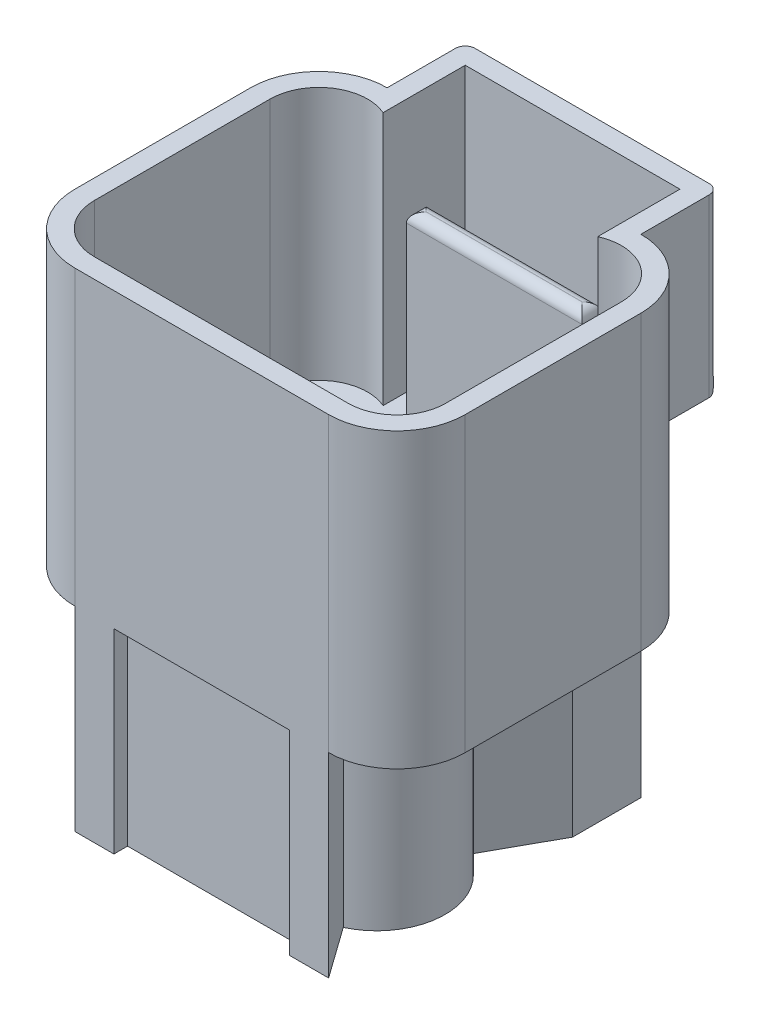
SolidWorks part; units mm, degrees
ref_plane "正面" through (0, 0, 0) normal (0, 0, 1) x (1, 0, 0)
ref_plane "平面" through (0, 0, 0) normal (0, 1, 0) x (1, 0, 0)
ref_plane "右側面" through (0, 0, 0) normal (1, 0, 0) x (0, 0, -1)
sketch "ｽｹｯﾁ1" plane through (0, 0, 0) normal (0, 0, 1) x (1, 0, 0)
  line L1 (0, 0) -> (20, 0)
  line L2 (0, 0) -> (0, 15)
  line L3 (0, 15) -> (20, 15)
  line L4 (20, 0) -> (20, 15)
  dimension "D1" = 20
  dimension "D2" = 15
extrude "ﾎﾞｽ - 押し出し1" add sketch "ｽｹｯﾁ1" along normal blind 16
fillet "ﾌｨﾚｯﾄ1" radius 3.5 4 edges at (0, 7.5, 16) (0, 7.5, 0) (20, 7.5, 16) (20, 7.5, 0)
sketch "ｽｹｯﾁ2" plane through (0, 0, 0) normal (0, 0, -1) x (-1, 0, 0)
  line L0 (-3.5, 0) -> (-3.5, 15) construction
  line L1 (-16.5, 15) -> (-3.5, 15)
  line L2 (-16.5, 15) -> (-16.5, 6)
  line L3 (-16.5, 6) -> (-3.5, 6)
  line L4 (-3.5, 15) -> (-3.5, 6)
  dimension "D1" = 9
extrude "ﾎﾞｽ - 押し出し2" add sketch "ｽｹｯﾁ2" along normal blind 4
fillet "ﾌｨﾚｯﾄ2" radius 0.5 3 edges at (3.5, 10.5, -4) (10, 6, -4) (16.5, 10.5, -4)
sketch "ｽｹｯﾁ3" plane through (0, 0, 0) normal (0, -1, 0) x (1, 0, 0)
  line L0 (3.5, 16) -> (5.6276, 13.0413)
  line L1 (16.5, 16) -> (14.6307, 13.3799)
  line L2 (3.5, 0) -> (3.5, 3.5)
  line L3 (3.5, 3.5) -> (5.8212, 7.2285)
  line L4 (16.5, 0) -> (16.5, 3.5)
  line L5 (16.5, 3.5) -> (14.5654, 6.9904)
  line L6 (3.5, 16) -> (16.5, 16)
  line L7 (3.5, 0) -> (16.5, 0)
  arc A2 (5.6276, 13.0413) -> (5.8212, 7.2285) centre (7.671, 10.1998) ccw
  arc A3 (14.5654, 6.9904) -> (14.6307, 13.3799) centre (13.1689, 10.1998) ccw
  point P0 (16.6689, 10.1998)
  point P3 (15.5597, 10.9307)
  point P6 (7.671, 10.1998)
  point P8 (13.1689, 10.1998)
  point P14 (10.0618, 10.9307)
extrude "ﾎﾞｽ - 押し出し3" add sketch "ｽｹｯﾁ3" along normal blind 10
sketch "ｽｹｯﾁ4" plane through (0, 0, 16) normal (0, 0, 1) x (1, 0, 0)
  line L0 (16.5, -10) -> (3.5, -10) construction
  line L1 (5.5, 0) -> (14.5, 0)
  line L2 (5.5, 0) -> (5.5, -10)
  line L3 (5.5, -10) -> (14.5, -10)
  line L4 (14.5, 0) -> (14.5, -10)
  line L5 (3.5, -10) -> (3.5, 0) construction
  line L6 (16.5, -10) -> (16.5, 0) construction
  dimension "D1" = 2
  dimension "D2" = 2
extrude "ｶｯﾄ - 押し出し2" cut sketch "ｽｹｯﾁ4" against normal blind 0.7
sketch "ｽｹｯﾁ5" plane through (0, -10, 0) normal (0, -1, 0) x (1, 0, 0)
  circle A0 centre (10, 10.4034) radius 4.1208
extrude "ｶｯﾄ - 押し出し3" cut sketch "ｽｹｯﾁ5" against normal blind 1
sketch "ｽｹｯﾁ6" plane through (0, 15, 0) normal (0, 1, 0) x (1, 0, 0)
  line L12 (15.5, 3) -> (4.5, 3)
  line L13 (4.5, 3) -> (4.5, -1.2087)
  line L14 (1, -3.5) -> (1, -12.5)
  line L15 (3.5, -15) -> (16.5, -15)
  line L16 (19, -12.5) -> (19, -3.5)
  line L17 (15.5, -1.2087) -> (15.5, 3)
  line L18 (15.5, 3) -> (4.5, 3)
  line L19 (4.5, 3) -> (4.5, -1.2087)
  line L20 (1, -3.5) -> (1, -12.5)
  line L21 (3.5, -15) -> (16.5, -15)
  line L22 (19, -12.5) -> (19, -3.5)
  line L23 (15.5, -1.2087) -> (15.5, 3)
  arc A12 (4.5, -1.2087) -> (1, -3.5) centre (3.5, -3.5) ccw
  arc A13 (1, -12.5) -> (3.5, -15) centre (3.5, -12.5) ccw
  arc A14 (16.5, -15) -> (19, -12.5) centre (16.5, -12.5) ccw
  arc A15 (19, -3.5) -> (15.5, -1.2087) centre (16.5, -3.5) ccw
  arc A16 (4.5, -1.2087) -> (1, -3.5) centre (3.5, -3.5) ccw
  arc A17 (1, -12.5) -> (3.5, -15) centre (3.5, -12.5) ccw
  arc A18 (16.5, -15) -> (19, -12.5) centre (16.5, -12.5) ccw
  arc A19 (19, -3.5) -> (15.5, -1.2087) centre (16.5, -3.5) ccw
  dimension "D1" = 1
extrude "ｶｯﾄ - 押し出し5" cut sketch "ｽｹｯﾁ6" against normal blind 13
sketch "ｽｹｯﾁ7" plane through (0, 2, 0) normal (0, 1, 0) x (1, 0, 0)
  line L0 (4.5, 0) -> (15.5, 0) construction
  line L1 (5.5, 0) -> (14.5, 0)
  line L2 (5.5, 0) -> (5.5, -1.0112)
  line L3 (5.5, -1.0112) -> (14.5, -1.0112)
  line L4 (14.5, 0) -> (14.5, -1.0112)
  line L5 (4.5, 3) -> (4.5, -1.2087) construction
  line L6 (15.5, -1.2087) -> (15.5, 3) construction
  dimension "D1" = 1
  dimension "D2" = 1
extrude "ﾎﾞｽ - 押し出し4" add sketch "ｽｹｯﾁ7" along normal blind 9
fillet "ﾌｨﾚｯﾄ3" radius 0.5 4 edges at (10, 11, 0) (14.5, 11, 0.5056) (10, 11, 1.0112) (5.5, 11, 0.5056)
sketch "ｽｹｯﾁ8" plane through (0, -10, 0) normal (0, -1, 0) x (1, 0, 0)
  line L12 (3.5, 0) -> (16.5, 0) construction
  line L14 (4.5, 1) -> (4.5, 0)
  line L15 (4.5, 0) -> (5.8384, 0)
  line L16 (5.8384, 1) -> (5.8384, 0)
  line L19 (15.5, 1) -> (15.5, 0)
  line L20 (15.5, 0) -> (14.187, 0)
  line L21 (14.187, 1) -> (14.187, 0)
  line L24 (5.9542, 14.3) -> (7.1452, 12.6438)
  line L25 (7.309, 7.7261) -> (4.5, 3.2142)
  line L26 (4.5, 3.2142) -> (4.5, 1)
  line L27 (4.5, 1) -> (15.5, 1)
  line L28 (15.5, 1) -> (15.5, 3.2414)
  line L29 (15.5, 3.2414) -> (13.0266, 7.7038)
  line L30 (12.9073, 12.686) -> (14.0588, 14.3)
  line L31 (14.0588, 14.3) -> (5.9542, 14.3)
  line L33 (6.5947, 6.5788) -> (4.5, 3.2142)
  line L34 (4.5, 3.2142) -> (4.5, 1)
  line L35 (5.8384, 1) -> (14.187, 1)
  line L36 (15.5, 1) -> (15.5, 3.2414)
  line L37 (15.5, 3.2414) -> (13.5669, 6.7291)
  arc A4 (7.1452, 12.6438) -> (7.309, 7.7261) centre (7.671, 10.1998) ccw
  arc A5 (13.0266, 7.7038) -> (12.9073, 12.686) centre (13.1689, 10.1998) ccw
  circle A6 centre (10, 10.4034) radius 5.1208
  arc A7 (6.5947, 6.5788) -> (13.5669, 6.7291) centre (10, 10.4034) ccw
  dimension "D1" = 1
  dimension "D2" = 1
extrude "ｶｯﾄ - 押し出し6" cut sketch "ｽｹｯﾁ8" against normal blind 9
